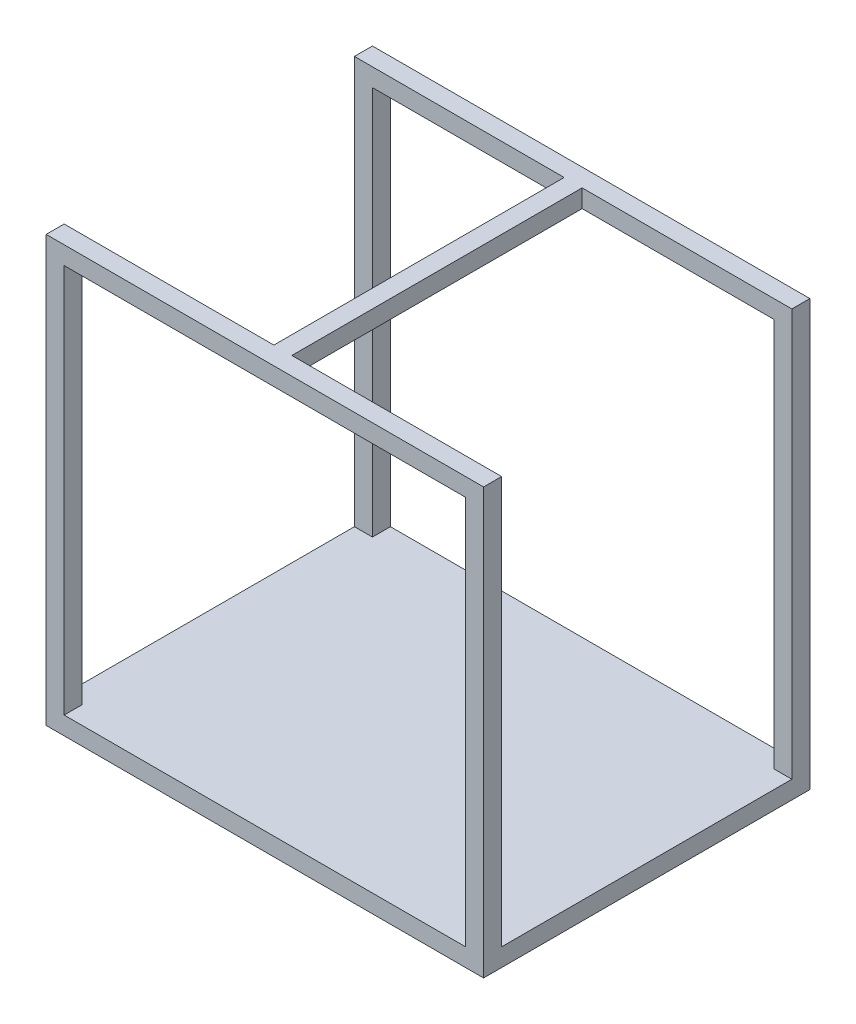
SolidWorks part; units mm, degrees
ref_plane "Front Plane" through (0, 0, 0) normal (0, 0, 1) x (1, 0, 0)
ref_plane "Top Plane" through (0, 0, 0) normal (0, 1, 0) x (1, 0, 0)
ref_plane "Right Plane" through (0, 0, 0) normal (1, 0, 0) x (0, 0, -1)
sketch "Sketch1" plane through (0, 0, 0) normal (1, 0, 0) x (0, 0, -1)
  line L0 (-410.8659, 304.373) -> (-410.8659, -295.702)
  line L1 (-410.8659, -295.702) -> (49.5091, -295.702)
  line L2 (49.5091, -295.702) -> (49.5091, 304.373)
  line L3 (49.5091, 304.373) -> (-410.8659, 304.373)
  line L4 (-385.4659, 278.973) -> (-385.4659, -270.302)
  line L5 (-385.4659, -270.302) -> (24.1091, -270.302)
  line L6 (24.1091, -270.302) -> (24.1091, 278.973)
  line L7 (24.1091, 278.973) -> (-385.4659, 278.973)
  dimension "D1" = 600.075
  dimension "D2" = 25.4
  dimension "D3" = 25.4
  dimension "D4" = 25.4
  dimension "D5" = 25.4
  dimension "D6" = 460.375
extrude "Boss-Extrude1" add sketch "Sketch1" against normal blind 617.22
sketch "Sketch3" plane through (0, 0, 410.8659) normal (0, 0, 1) x (1, 0, 0)
  line L0 (-591.82, 278.973) -> (-591.82, -270.302)
  line L1 (-591.82, -270.302) -> (-25.4, -270.302)
  line L2 (-25.4, -270.302) -> (-25.4, 278.973)
  line L3 (-25.4, 278.973) -> (-591.82, 278.973)
  line L4 (-617.22, 304.373) -> (0, 304.373) construction
  line L5 (-617.22, 304.373) -> (-617.22, -295.702) construction
  line L6 (0, 304.373) -> (0, -295.702) construction
  line L7 (-617.22, -295.702) -> (0, -295.702) construction
  dimension "D1" = 25.4
  dimension "D2" = 25.4
  dimension "D3" = 25.4
  dimension "D4" = 25.4
extrude "Cut-Extrude1" cut sketch "Sketch3" against normal through all
sketch "Sketch4" plane through (0, 304.373, 0) normal (0, 1, 0) x (1, 0, 0)
  line L0 (-617.22, 24.1091) -> (-321.31, 24.1091)
  line L1 (-617.22, 49.5091) -> (-617.22, -410.8659) construction
  line L2 (-321.31, 24.1091) -> (-321.31, -385.4659)
  line L3 (-321.31, -385.4659) -> (-617.22, -385.4659)
  line L4 (-617.22, -385.4659) -> (-617.22, 24.1091)
  line L5 (0, 24.1091) -> (-295.91, 24.1091)
  line L6 (0, 49.5091) -> (0, -410.8659) construction
  line L7 (-295.91, 24.1091) -> (-295.91, -385.4659)
  line L8 (-295.91, -385.4659) -> (0, -385.4659)
  line L9 (0, -385.4659) -> (0, 24.1091)
  line L11 (-617.22, 49.5091) -> (0, 49.5091) construction
  dimension "D1" = 25.4
  dimension "D2" = 295.91
  dimension "D3" = 25.4
  dimension "D4" = 25.4
  dimension "D5" = 25.4
extrude "Cut-Extrude2" cut sketch "Sketch4" against normal up to next
sketch "Sketch5" plane through (0, -270.302, 0) normal (0, 1, 0) x (1, 0, 0)
  line L3 (-617.22, -410.8659) -> (0, -410.8659) construction
  line L6 (-25.4, -410.8659) -> (-591.82, -410.8659)
  line L7 (-591.82, -410.8659) -> (-591.82, -385.4659)
  line L8 (-617.22, -385.4659) -> (-321.31, -385.4659) construction
  line L9 (-591.82, -385.4659) -> (-617.22, -385.4659)
  line L10 (-617.22, -385.4659) -> (-617.22, -179.0909)
  line L11 (-617.22, -385.4659) -> (-617.22, 24.1091) construction
  line L12 (-617.22, -179.0909) -> (0, -179.0909)
  line L13 (-25.4, -410.8659) -> (-25.4, -385.4659)
  line L14 (-295.91, -385.4659) -> (0, -385.4659) construction
  line L15 (-25.4, -385.4659) -> (0, -385.4659)
  line L16 (0, -385.4659) -> (0, -179.0909)
  line L17 (0, -385.4659) -> (0, 24.1091) construction
  point P3 (0, 0)
  point P4 (-6.3443, -179.0909)
